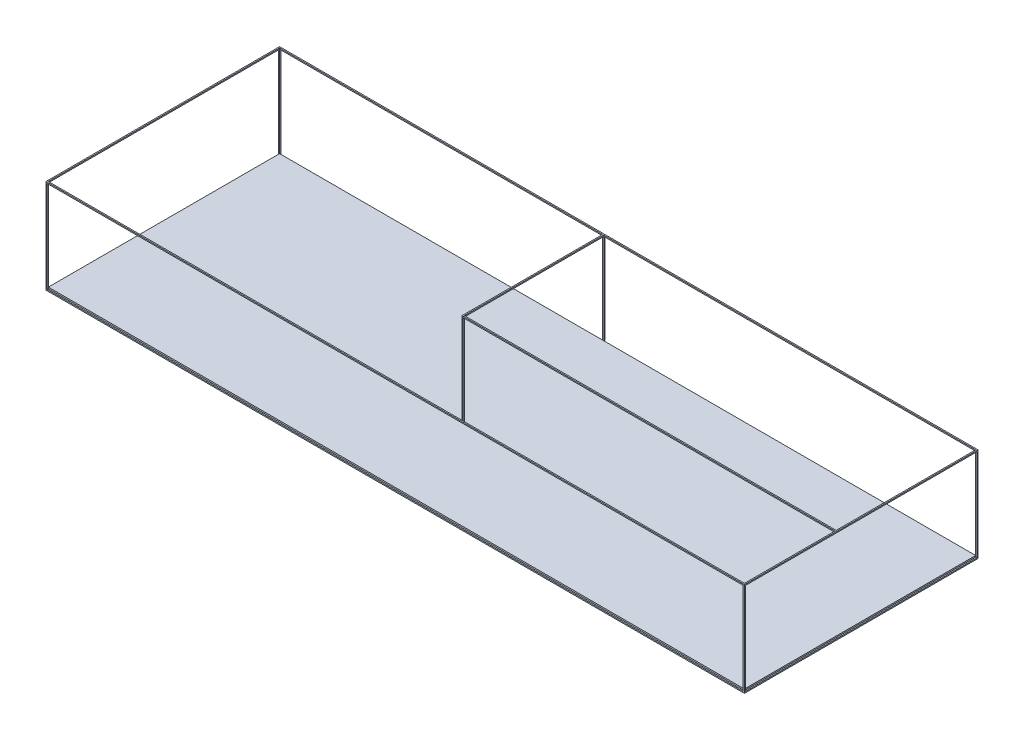
SolidWorks part; units mm, degrees
ref_plane "Alzado" through (0, 0, 0) normal (0, 0, 1) x (1, 0, 0)
ref_plane "Planta" through (0, 0, 0) normal (0, 1, 0) x (1, 0, 0)
ref_plane "Vista lateral" through (0, 0, 0) normal (1, 0, 0) x (0, 0, -1)
sketch "Croquis1" plane through (0, 0, 0) normal (0, 1, 0) x (1, 0, 0)
  line L1 (-7500, -2500) -> (7500, -2500)
  line L2 (-7500, -2500) -> (-7500, 2500)
  line L3 (-7500, 2500) -> (7500, 2500)
  line L4 (7500, -2500) -> (7500, 2500)
  point P0 (0, 0)
  dimension "D1" = 5000
  dimension "D2" = 15000
sketch "Croquis2" plane through (0, 0, 0) normal (1, 0, 0) x (0, 0, -1)
  line L0 (-2500, 0) -> (2500, 0) construction
  line L1 (-2512.7, -12.7) -> (-2487.3, -12.7)
  line L2 (-2512.7, -12.7) -> (-2512.7, 12.7)
  line L3 (-2512.7, 12.7) -> (-2487.3, 12.7)
  line L4 (-2487.3, -12.7) -> (-2487.3, 12.7)
  line L5 (-2512.7, -12.7) -> (-2487.3, 12.7) construction
  line L6 (-2512.7, 12.7) -> (-2487.3, -12.7) construction
  line L7 (-2500, 0) -> (2500, 0) construction
  point P0 (-2500, 0)
  dimension "D1" = 25.4
  dimension "D2" = 25.4
sweep "Barrer1" add profiles "Croquis2" path "Croquis1"
sketch "Croquis3" plane through (0, 12.7, 0) normal (0, 1, 0) x (1, 0, 0)
  line L1 (-7512.7, 2512.7) -> (-7487.3, 2512.7)
  line L2 (-7512.7, 2512.7) -> (-7512.7, 2487.3)
  line L3 (-7512.7, 2487.3) -> (-7487.3, 2487.3)
  line L4 (-7487.3, 2512.7) -> (-7487.3, 2487.3)
  line L5 (-7512.7, -2512.7) -> (-7487.3, -2512.7)
  line L6 (-7512.7, -2512.7) -> (-7512.7, -2487.3)
  line L7 (-7512.7, -2487.3) -> (-7487.3, -2487.3)
  line L8 (-7487.3, -2512.7) -> (-7487.3, -2487.3)
  line L9 (7487.3, -2487.3) -> (7512.7, -2487.3)
  line L10 (7487.3, -2487.3) -> (7487.3, -2512.7)
  line L11 (7487.3, -2512.7) -> (7512.7, -2512.7)
  line L12 (7512.7, -2487.3) -> (7512.7, -2512.7)
  line L13 (7487.3, 2487.3) -> (7512.7, 2487.3)
  line L14 (7487.3, 2487.3) -> (7487.3, 2512.7)
  line L15 (7487.3, 2512.7) -> (7512.7, 2512.7)
  line L16 (7512.7, 2487.3) -> (7512.7, 2512.7)
extrude "Saliente-Extruir1" add sketch "Croquis3" along normal blind 2000
sketch "Croquis4" plane through (0, 0, -2487.3) normal (0, 0, 1) x (1, 0, 0)
  line L0 (-7487.3, 2012.7) -> (-7487.3, 12.7) construction
  line L1 (-7512.7, 2012.7) -> (-7487.3, 2012.7)
  line L2 (-7512.7, 2012.7) -> (-7512.7, 1987.3)
  line L3 (-7512.7, 1987.3) -> (-7487.3, 1987.3)
  line L4 (-7487.3, 2012.7) -> (-7487.3, 1987.3)
  dimension "D1" = 25.4
extrude "Saliente-Extruir2" add sketch "Croquis4" along normal blind 4993
mirror "Simetría1" about plane through (0, 0, 0) normal (1, 0, 0) of "Saliente-Extruir2"
sketch "Croquis5" plane through (7487.3, 0, 0) normal (-1, 0, 0) x (0, 0, 1)
  line L1 (2512.7, 2012.7) -> (2487.3, 2012.7)
  line L2 (2512.7, 2012.7) -> (2512.7, 1987.3)
  line L3 (2512.7, 1987.3) -> (2487.3, 1987.3)
  line L4 (2487.3, 2012.7) -> (2487.3, 1987.3)
  line L5 (-2512.7, 2012.7) -> (-2487.3, 2012.7)
  line L6 (-2512.7, 2012.7) -> (-2512.7, 1987.3)
  line L7 (-2512.7, 1987.3) -> (-2487.3, 1987.3)
  line L8 (-2487.3, 2012.7) -> (-2487.3, 1987.3)
extrude "Saliente-Extruir3" add sketch "Croquis5" along normal blind 14977
sketch "Croquis8" plane through (0, 2012.7, 0) normal (0, 1, 0) x (1, 0, 0)
  line L0 (-512.7, 2487.3) -> (-512.7, -512.7)
  line L1 (-7487.3, 2487.3) -> (7487.3, 2487.3) construction
  line L2 (-512.7, -512.7) -> (7487.3, -512.7)
  line L3 (7487.3, 2487.3) -> (7487.3, -2487.3) construction
  line L4 (-512.7, 2487.3) -> (-538.1, 2487.3)
  line L5 (-538.1, 2487.3) -> (-538.1, -538.1)
  line L6 (-538.1, -538.1) -> (7487.3, -538.1)
  line L7 (7487.3, -538.1) -> (7487.3, -512.7)
  dimension "D1" = 3000
  dimension "D2" = 8000
  dimension "D3" = 25.4
  dimension "D4" = 25.4
extrude "Saliente-Extruir5" add sketch "Croquis8" against normal up to surface (2025.4 mm away) up to face at (7500, -12.7, 0)
sketch "Croquis9" plane through (-538.1, 0, 0) normal (-1, 0, 0) x (0, 0, 1)
  line L0 (-2487.3, 1987.3) -> (512.7, 1987.3)
  line L1 (-2487.3, 12.7) -> (-2487.3, 1987.3) construction
  line L3 (-2512.7, 2012.7) -> (2512.7, 2012.7) construction
  line L4 (538.1, -12.7) -> (538.1, 2012.7) construction
  line L5 (512.7, 1987.3) -> (512.7, -12.7)
  line L6 (512.7, -12.7) -> (-2487.3, -12.7)
  line L7 (-2512.7, -12.7) -> (2512.7, -12.7) construction
  line L8 (-2487.3, -12.7) -> (-2487.3, 1987.3)
  dimension "D1" = 25.4
  dimension "D2" = 25.4
extrude "Cortar-Extruir2" cut sketch "Croquis9" against normal blind 3769
sketch "Croquis11" plane through (0, 0, 538.1) normal (0, 0, 1) x (1, 0, 0)
  line L0 (-512.7, 1987.3) -> (-512.7, 12.7)
  line L1 (-7487.3, 1987.3) -> (7487.3, 1987.3) construction
  line L2 (-7487.3, 12.7) -> (0, 12.7) construction
  line L3 (-538.1, -12.7) -> (-538.1, 2012.7) construction
  line L4 (-512.7, 1987.3) -> (7487.3, 1987.3)
  line L5 (7487.3, 1987.3) -> (7487.3, -12.7)
  line L6 (7487.3, -12.7) -> (-512.7, -12.7)
  line L7 (-7512.7, -12.7) -> (0, -12.7) construction
  line L8 (-512.7, -12.7) -> (-512.7, 12.7)
  dimension "D1" = 25.4
extrude "Cortar-Extruir3" cut sketch "Croquis11" against normal blind 1551
sketch "Croquis12" plane through (0, -12.7, 0) normal (0, -1, 0) x (1, 0, 0)
  line L1 (-7487.3, 2487.3) -> (7487.3, 2487.3)
  line L2 (-7487.3, 2487.3) -> (-7487.3, -2487.3)
  line L3 (-7487.3, -2487.3) -> (7487.3, -2487.3)
  line L4 (7487.3, 2487.3) -> (7487.3, -2487.3)
extrude "Saliente-Extruir7" add sketch "Croquis12" against normal blind 57 separate body
sketch "Croquis13" plane through (0, 1987.3, 0) normal (0, -1, 0) x (1, 0, 0)
  line L0 (-7487.3, -2512.7) -> (7487.3, -2512.7) construction
  line L1 (-512.7, -2487.3) -> (-537.9051, -2487.3)
  line L2 (-512.7, -2487.3) -> (-512.7, -2512.7)
  line L3 (-512.7, -2512.7) -> (-537.9051, -2512.7)
  line L4 (-537.9051, -2487.3) -> (-537.9051, -2512.7)
extrude "Saliente-Extruir8" add sketch "Croquis13" along normal blind 1950
